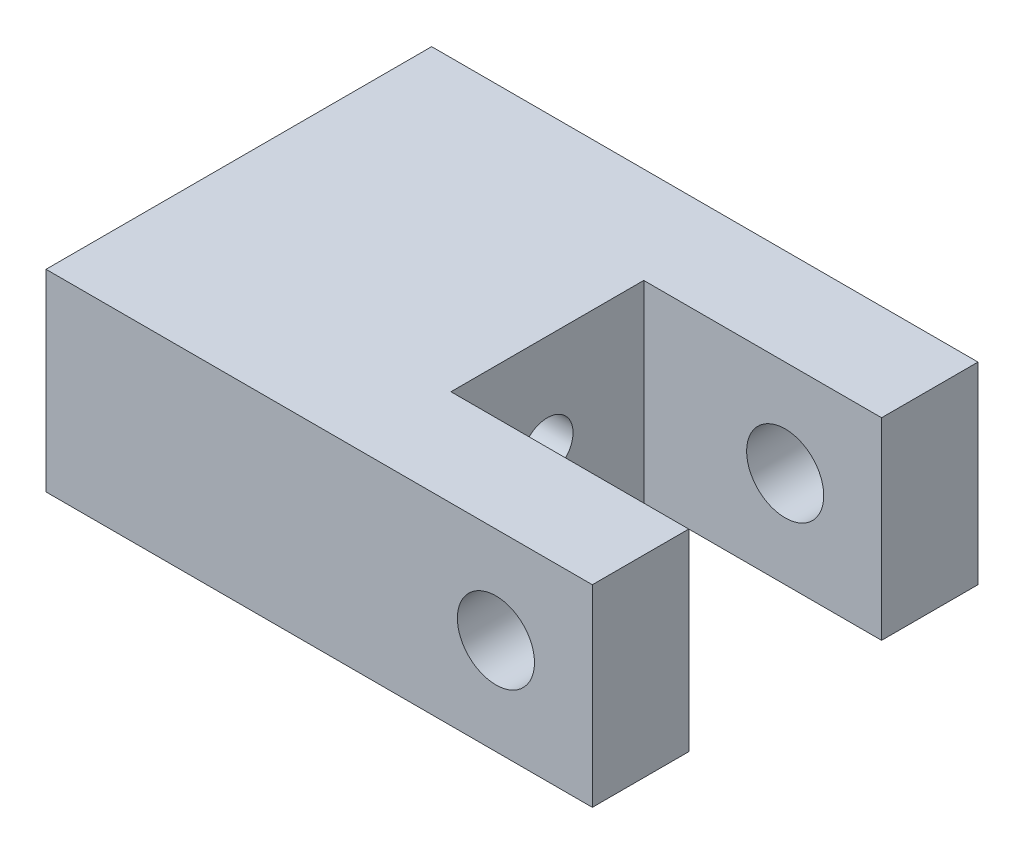
SolidWorks part; units mm, degrees
ref_plane "Front Plane" through (0, 0, 0) normal (0, 0, 1) x (1, 0, 0)
ref_plane "Top Plane" through (0, 0, 0) normal (0, 1, 0) x (1, 0, 0)
ref_plane "Right Plane" through (0, 0, 0) normal (1, 0, 0) x (0, 0, -1)
sketch "Sketch1" plane through (0, 0, 0) normal (0, 1, 0) x (1, 0, 0)
  line L0 (0, 0) -> (0, 30) construction
  line L1 (15, 0) -> (-70, 0) construction
  line L2 (15, -30) -> (15, 30)
  line L3 (15, 30) -> (-70, 30)
  line L4 (-70, -30) -> (-70, 30)
  line L5 (15, -30) -> (-70, -30)
  dimension "D1" = 60
  dimension "D2" = 85
  dimension "D3" = 70
extrude "Extrude1" add sketch "Sketch1" along normal mid plane 30
hole_wizard "Ø12.0 (12) Diameter Hole1" positions "Sketch3" profile "Sketch2" hole size "Ø12.0" standard "Ansi Metric" end condition through all
sketch "Sketch3" plane through (0, 0, 30) normal (0, 0, 1) x (1, 0, 0)
  point P0 (0, 0)
sketch "Sketch2" plane through (0, 0, 30) normal (1, 0, 0) x (0, -1, 0)
  line L0 (0, 0) -> (0, 60)
  line L1 (0, 60) -> (6, 60)
  line L2 (6, 60) -> (6, 0)
  line L5 (6, 0) -> (0, 0)
  line L11 (0, -6.35) -> (0, 107.95) construction
  dimension "Thru Hole Dia." = 12
  dimension "Thru Hole Depth" = 60
sketch "Sketch4" plane through (0, 15, 0) normal (0, 1, 0) x (1, 0, 0)
  line L0 (15, -30) -> (15, 30) construction
  line L1 (15, 0) -> (-22, 0) construction
  line L2 (15, -15) -> (15, 15)
  line L3 (15, 15) -> (-22, 15)
  line L4 (-22, -15) -> (-22, 15)
  line L5 (-70, 30) -> (-70, -30) construction
  line L6 (15, -15) -> (-22, -15)
  dimension "D1" = 48
  dimension "D2" = 30
extrude "Cut-Extrude1" cut sketch "Sketch4" against normal through all
hole_wizard "Ø8.0 (8) Diameter Hole1" positions "Sketch7" profile "Sketch8" hole size "Ø8.0" standard "Ansi Metric" end condition through all
sketch "Sketch7" plane through (-70, 0, 0) normal (-1, 0, 0) x (0, 0, 1)
  point P0 (0, 0)
sketch "Sketch8" plane through (-70, 0, 0) normal (0, 1, 0) x (0, 0, 1)
  line L0 (0, 0) -> (0, 85)
  line L1 (0, 85) -> (4, 85)
  line L2 (4, 85) -> (4, 0)
  line L5 (4, 0) -> (0, 0)
  line L11 (0, -6.35) -> (0, 107.95) construction
  dimension "Thru Hole Dia." = 8
  dimension "Thru Hole Depth" = 85
hole_wizard "M12x1.75 Tapped Hole1" positions "Sketch10" profile "Sketch9" tap size "M12x1.75" standard "Ansi Metric"
sketch "Sketch10" plane through (-70, 0, 0) normal (-1, 0, 0) x (0, 0, 1)
  line L0 (0, 0) -> (-12.1647, 0) construction
  circle A0 centre (0, 0) radius 4 construction
  point P0 (-20, 0)
  dimension "D1" = 20
sketch "Sketch9" plane through (-70, 0, -20) normal (0, 1, 0) x (0, 0, 1)
  line L0 (0, 0) -> (0, 30.3144)
  line L1 (0, 30.3144) -> (5.1, 27.25)
  line L2 (5.1, 27.25) -> (5.1, 0)
  line L5 (5.1, 0) -> (0, 0)
  line L10 (0, 30.3144) -> (-5.1, 27.25) construction
  line L11 (0, -6.35) -> (0, 107.95) construction
  dimension "Tap Drill Dia." = 10.2
  dimension "Tap Drill Depth" = 27.25
  dimension "Drill Angle" = 118
cosmetic thread "Hole Thread1" parameters "D1"=22, "D2"=12
mirror "Mirror1" about plane through (0, 0, 0) normal (0, 0, 1) of "M12x1.75 Tapped Hole1"
